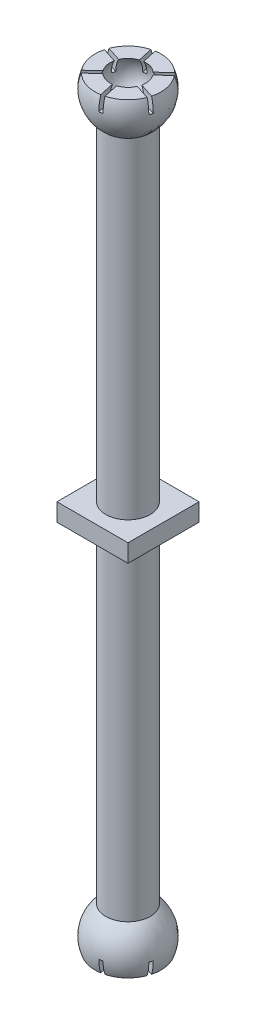
SolidWorks part; units mm, degrees
ref_plane "Front Plane" through (0, 0, 0) normal (0, 0, 1) x (1, 0, 0)
ref_plane "Top Plane" through (0, 0, 0) normal (0, 1, 0) x (1, 0, 0)
ref_plane "Right Plane" through (0, 0, 0) normal (1, 0, 0) x (0, 0, -1)
sketch "Sketch1" plane through (0, 0, 0) normal (0, 1, 0) x (1, 0, 0)
  circle A0 centre (0, 0) radius 25
  dimension "D1" = 50
extrude "Boss-Extrude1" add sketch "Sketch1" along normal mid plane 826
ref_plane "Plane1" through (0, 413, 0) normal (0, 1, 0) x (1, 0, 0)
ref_plane "Plane2" through (0, -413, 0) normal (0, -1, 0) x (-1, 0, 0)
sketch "Sketch10" plane through (0, 413, 0) normal (0, 1, 0) x (1, 0, 0)
  line L0 (0, 40) -> (0, -40)
  arc A0 (0, 40) -> (0, -40) centre (0, 0) ccw
  dimension "D1" = 40
revolve "Revolve4" add sketch "Sketch10" angle 360 about L0
sketch "Sketch11" plane through (0, -413, 0) normal (0, -1, 0) x (1, 0, 0)
  line L0 (0, 40) -> (0, -40)
  arc A0 (0, 40) -> (0, -40) centre (0, 0) ccw
  circle A1 centre (0, 0) radius 40 construction
revolve "Revolve5" add sketch "Sketch11" angle 360 about L0
ref_plane "Plane8" through (0, -428, 0) normal (0, -1, 0) x (-1, 0, 0)
ref_plane "Plane9" through (0, 428, 0) normal (0, 1, 0) x (1, 0, 0)
sketch "Sketch12" plane through (0, -428, 0) normal (0, -1, 0) x (-1, 0, 0)
  circle A0 centre (0, 0) radius 49.4225
extrude "Cut-Extrude5" cut sketch "Sketch12" along normal through all
sketch "Sketch13" plane through (0, 428, 0) normal (0, 1, 0) x (1, 0, 0)
  circle A0 centre (0, 0) radius 55.4386
extrude "Cut-Extrude6" cut sketch "Sketch13" along normal through all
sketch "Sketch14" plane through (0, 413, 0) normal (0, 1, 0) x (1, 0, 0)
  line L0 (-14.4133, -20.4268) -> (14.4133, 20.4268)
  arc A0 (14.4133, 20.4268) -> (-14.4133, -20.4268) centre (0, 0) ccw
  dimension "D1" = 25
revolve "Cut-Revolve1" cut sketch "Sketch14" angle 360 about L0
sketch "Sketch15" plane through (0, 413, 0) normal (0, 1, 0) x (1, 0, 0)
  line L6 (-2.694, 2.9567) -> (-40.3349, 14.9415)
  line L9 (2.694, -2.9567) -> (40.3349, -14.9415)
  line L10 (-1.2136, -3.8115) -> (7.2277, -42.4018)
  line L11 (-3.9076, -0.8548) -> (-33.1072, -27.4603)
  line L14 (1.2136, 3.8115) -> (30.4132, 30.417)
  line L16 (2.694, -2.9567) -> (11.1353, -41.5471)
  line L18 (3.9076, 0.8548) -> (41.5485, -11.1301)
  line L19 (1.2136, 3.8115) -> (-7.2277, 42.4018)
  line L36 (-2.694, 2.9567) -> (-11.1353, 41.5471)
  line L37 (3.9076, 0.8548) -> (33.1072, 27.4603)
  line L38 (-3.9076, -0.8548) -> (-41.5485, 11.1301)
  line L41 (-1.2136, -3.8115) -> (-30.4132, -30.417)
  arc A0 (-33.1072, -27.4603) -> (-30.4132, -30.417) centre (0, 0) ccw
  arc A1 (-40.3349, 14.9415) -> (-41.5485, 11.1301) centre (0, 0) ccw
  arc A2 (-7.2277, 42.4018) -> (-11.1353, 41.5471) centre (0, 0) ccw
  arc A3 (33.1072, 27.4603) -> (30.4132, 30.417) centre (0, 0) ccw
  arc A4 (40.3349, -14.9415) -> (41.5485, -11.1301) centre (0, 0) ccw
  arc A5 (7.2277, -42.4018) -> (11.1353, -41.5471) centre (0, 0) ccw
  point P11 (0, 0)
extrude "Cut-Extrude7" cut sketch "Sketch15" along normal through all
sketch "Sketch16" plane through (0, -413, 0) normal (0, -1, 0) x (-1, 0, 0)
  line L0 (-15.5605, -19.5671) -> (15.5605, 19.5671)
  arc A0 (15.5605, 19.5671) -> (-15.5605, -19.5671) centre (0, 0) ccw
  dimension "D1" = 25
revolve "Cut-Revolve2" cut sketch "Sketch16" angle 360 about L0
sketch "Sketch17" plane through (0, -413, 0) normal (0, -1, 0) x (-1, 0, 0)
  line L12 (-2.694, -2.9567) -> (-11.1353, -41.5471)
  line L13 (-7.2277, -42.4018) -> (1.2136, -3.8115)
  line L14 (1.2136, -3.8115) -> (30.4132, -30.417)
  line L15 (33.1072, -27.4603) -> (3.9076, -0.8548)
  line L16 (3.9076, -0.8548) -> (41.5485, 11.1301)
  line L17 (40.3349, 14.9415) -> (2.694, 2.9567)
  line L18 (2.694, 2.9567) -> (11.1353, 41.5471)
  line L19 (7.2277, 42.4018) -> (-1.2136, 3.8115)
  line L20 (-1.2136, 3.8115) -> (-30.4132, 30.417)
  line L21 (-33.1072, 27.4603) -> (-3.9076, 0.8548)
  line L22 (-3.9076, 0.8548) -> (-41.5485, -11.1301)
  line L23 (-40.3349, -14.9415) -> (-2.694, -2.9567)
  line L24 (-2.694, -2.9567) -> (-11.1353, -41.5471)
  line L25 (-7.2277, -42.4018) -> (1.2136, -3.8115)
  line L26 (1.2136, -3.8115) -> (30.4132, -30.417)
  line L27 (33.1072, -27.4603) -> (3.9076, -0.8548)
  line L28 (3.9076, -0.8548) -> (41.5485, 11.1301)
  line L29 (40.3349, 14.9415) -> (2.694, 2.9567)
  line L30 (2.694, 2.9567) -> (11.1353, 41.5471)
  line L31 (7.2277, 42.4018) -> (-1.2136, 3.8115)
  line L32 (-1.2136, 3.8115) -> (-30.4132, 30.417)
  line L33 (-33.1072, 27.4603) -> (-3.9076, 0.8548)
  line L34 (-3.9076, 0.8548) -> (-41.5485, -11.1301)
  line L35 (-40.3349, -14.9415) -> (-2.694, -2.9567)
  arc A6 (-11.1353, -41.5471) -> (-7.2277, -42.4018) centre (0, 0) ccw
  arc A7 (30.4132, -30.417) -> (33.1072, -27.4603) centre (0, 0) ccw
  arc A8 (41.5485, 11.1301) -> (40.3349, 14.9415) centre (0, 0) ccw
  arc A9 (11.1353, 41.5471) -> (7.2277, 42.4018) centre (0, 0) ccw
  arc A10 (-30.4132, 30.417) -> (-33.1072, 27.4603) centre (0, 0) ccw
  arc A11 (-41.5485, -11.1301) -> (-40.3349, -14.9415) centre (0, 0) ccw
  arc A12 (-11.1353, -41.5471) -> (-7.2277, -42.4018) centre (0, 0) ccw
  arc A13 (30.4132, -30.417) -> (33.1072, -27.4603) centre (0, 0) ccw
  arc A14 (41.5485, 11.1301) -> (40.3349, 14.9415) centre (0, 0) ccw
  arc A15 (11.1353, 41.5471) -> (7.2277, 42.4018) centre (0, 0) ccw
  arc A16 (-30.4132, 30.417) -> (-33.1072, 27.4603) centre (0, 0) ccw
  arc A17 (-41.5485, -11.1301) -> (-40.3349, -14.9415) centre (0, 0) ccw
  dimension "D1" = 0
extrude "Cut-Extrude8" cut sketch "Sketch17" along normal through all
sketch "Sketch18" plane through (0, 0, 0) normal (0, 1, 0) x (1, 0, 0)
  line L1 (-40, -40) -> (40, -40)
  line L2 (-40, -40) -> (-40, 40)
  line L3 (-40, 40) -> (40, 40)
  line L4 (40, -40) -> (40, 40)
  line L5 (-40, -40) -> (40, 40) construction
  line L6 (-40, 40) -> (40, -40) construction
  point P0 (0, 0)
  dimension "D1" = 80
  dimension "D2" = 80
extrude "Boss-Extrude2" add sketch "Sketch18" along normal mid plane 20
